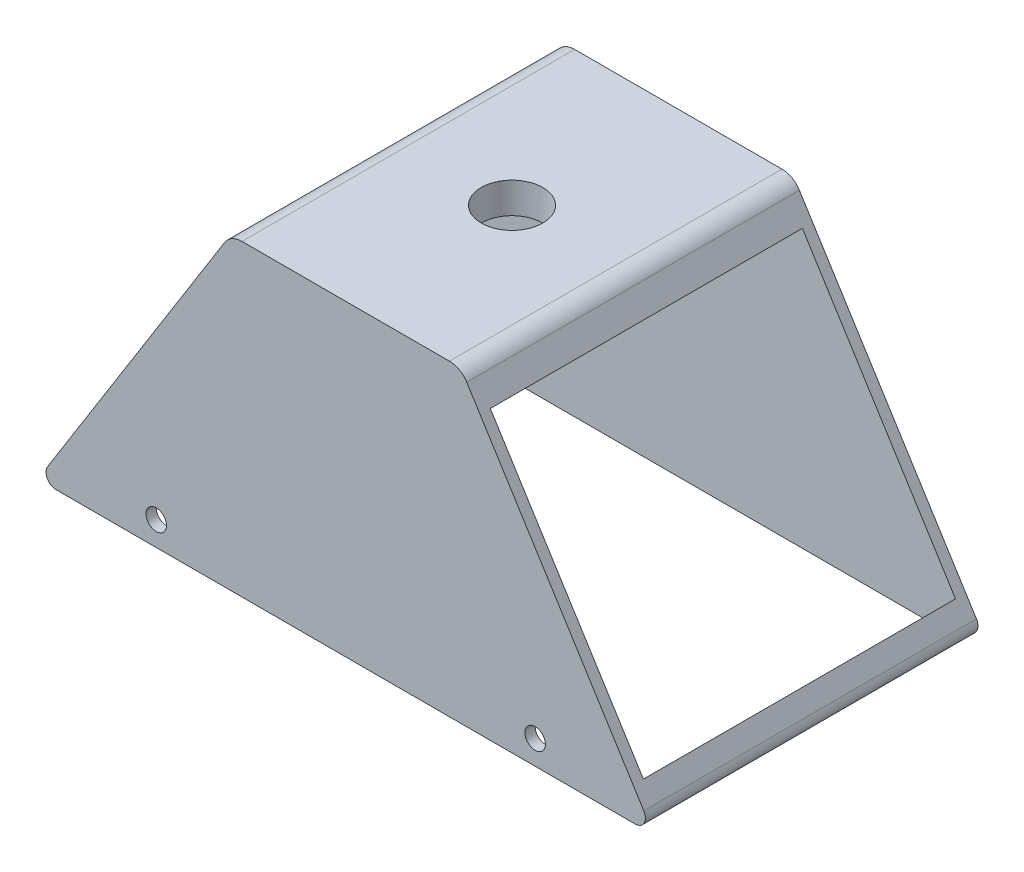
SolidWorks part; units mm, degrees
ref_plane "Front Plane" through (0, 0, 0) normal (0, 0, 1) x (1, 0, 0)
ref_plane "Top Plane" through (0, 0, 0) normal (0, 1, 0) x (1, 0, 0)
ref_plane "Right Plane" through (0, 0, 0) normal (1, 0, 0) x (0, 0, -1)
sketch "Sketch1" plane through (0, 0, 0) normal (0, 0, 1) x (1, 0, 0)
  line L1 (-46.0372, 83.9136) -> (66.0372, 83.9136)
  line L3 (10, -66.0864) -> (160, -66.0864)
  line L4 (10, -66.0864) -> (-140, -66.0864)
  line L5 (-46.0372, 83.9136) -> (-140, -66.0864)
  line L6 (66.0372, 83.9136) -> (160, -66.0864)
  dimension "D1" = 150
  dimension "D2" = 150
  dimension "D3" = 150
  dimension "D4" = 177
  dimension "D5" = 177
extrude "Boss-Extrude1" add sketch "Sketch1" along normal blind 162
sketch "Sketch2" plane through (0, 83.9136, 0) normal (0, 1, 0) x (1, 0, 0)
  line L0 (-46.0372, -81) -> (66.0372, -81) construction
  line L1 (-46.0372, -162) -> (-46.0372, 0) construction
  line L2 (66.0372, -162) -> (66.0372, 0) construction
  line L3 (10, 0) -> (10, -162) construction
  line L4 (66.0372, 0) -> (-46.0372, 0) construction
  line L5 (66.0372, -162) -> (-46.0372, -162) construction
  circle A0 centre (10, -81) radius 15
  dimension "D1" = 30
extrude "Cut-Extrude1" cut sketch "Sketch2" against normal blind 15
sketch "Sketch4" plane through (0, -66.0864, 0) normal (0, -1, 0) x (1, 0, 0)
  line L0 (-140, 162) -> (160, 162) construction
  line L1 (-130, 157) -> (150, 157)
  line L2 (-130, 157) -> (-130, 5)
  line L3 (-130, 5) -> (150, 5)
  line L4 (150, 157) -> (150, 5)
  line L5 (-140, 162) -> (-140, 0) construction
  line L7 (160, 162) -> (160, 0) construction
  line L8 (-140, 0) -> (160, 0) construction
  dimension "D1" = 5
  dimension "D2" = 10
  dimension "D3" = 10
  dimension "D4" = 5
extrude "Cut-Extrude3" cut sketch "Sketch4" against normal blind 135
fillet "Fillet2" radius 10 2 edges at (-46.0372, 83.9136, 81) (66.0372, 83.9136, 81)
fillet "Fillet3" radius 5 2 edges at (160, -66.0864, 81) (-140, -66.0864, 81)
sketch "Sketch5" plane through (0, 0, 162) normal (0, 0, 1) x (1, 0, 0)
  line L0 (10, -66.0864) -> (10, 83.9136) construction
  line L1 (-130.9679, -66.0864) -> (150.9679, -66.0864) construction
  line L2 (60.5014, 83.9136) -> (-40.5014, 83.9136) construction
  line L3 (10, -66.0864) -> (10, -54.3506) construction
  line L4 (102.2753, -54.3506) -> (10, -54.3506) construction
  circle A0 centre (102.2753, -54.3506) radius 5
  circle A1 centre (-82.2753, -54.3506) radius 5
  dimension "D3" = 10
  dimension "D1" = 11.7358
  dimension "D2" = 92.2753
extrude "Cut-Extrude4" cut sketch "Sketch5" against normal blind 135
